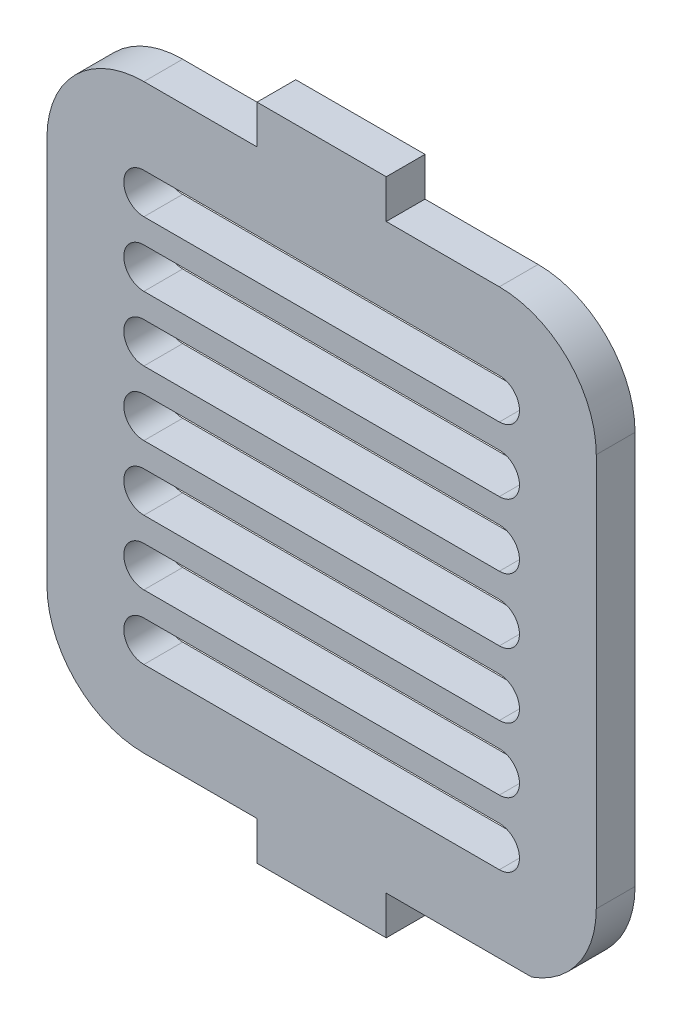
SolidWorks part; units mm, degrees
ref_plane "Front Plane" through (0, 0, 0) normal (0, 0, 1) x (1, 0, 0)
ref_plane "Top Plane" through (0, 0, 0) normal (0, 1, 0) x (1, 0, 0)
ref_plane "Right Plane" through (0, 0, 0) normal (1, 0, 0) x (0, 0, -1)
sketch "Sketch1" plane through (0, 0, 0) normal (0, 0, 1) x (1, 0, 0)
  line L0 (10, 45) -> (10, 51)
  line L3 (10, 51) -> (-10, 51)
  line L4 (-10, 51) -> (-10, 45)
  line L5 (10, -45) -> (10, -51)
  line L6 (10, -51) -> (-10, -51)
  line L7 (-10, -51) -> (-10, -45)
  line L9 (42.5, 30) -> (42.5, -30.8579)
  line L11 (-42.5, -30) -> (-42.5, 30)
  line L12 (-27.5, 30) -> (27.5, 30) construction
  line L13 (-27.5, 33.1127) -> (27.5, 33.1127)
  line L14 (-27.5, 26.8873) -> (27.5, 26.8873)
  line L15 (-27.5, 20) -> (27.5, 20) construction
  line L16 (-27.5, 23.1127) -> (27.5, 23.1127)
  line L17 (-27.5, 16.8873) -> (27.5, 16.8873)
  line L18 (-27.5, 10) -> (27.5, 10) construction
  line L19 (-27.5, 13.1127) -> (27.5, 13.1127)
  line L20 (-27.5, 6.8873) -> (27.5, 6.8873)
  line L21 (-27.5, 0) -> (27.5, 0) construction
  line L22 (-27.5, 3.1127) -> (27.5, 3.1127)
  line L23 (-27.5, -3.1127) -> (27.5, -3.1127)
  line L24 (-27.5, -10) -> (27.5, -10) construction
  line L25 (-27.5, -6.8873) -> (27.5, -6.8873)
  line L26 (-27.5, -13.1127) -> (27.5, -13.1127)
  line L27 (-27.5, -20) -> (27.5, -20) construction
  line L28 (-27.5, -16.8873) -> (27.5, -16.8873)
  line L29 (-27.5, -23.1127) -> (27.5, -23.1127)
  line L30 (-27.5, -30) -> (27.5, -30) construction
  line L31 (-27.5, -26.8873) -> (27.5, -26.8873)
  line L32 (-27.5, -33.1127) -> (27.5, -33.1127)
  line L33 (-27.5, 45) -> (27.5, 45)
  line L34 (-10, 45) -> (10, 45)
  line L35 (-27.5, -45) -> (32.5, -45)
  line L36 (-10, -45) -> (10, -45)
  arc A0 (-42.5, 30) -> (-27.5, 45) centre (-27.5, 30) cw
  arc A1 (-27.5, -45) -> (-42.5, -30) centre (-27.5, -30) cw
  arc A2 (42.5, -30.8579) -> (32.5, -45) centre (27.5, -30.8579) cw
  arc A3 (27.5, 45) -> (42.5, 30) centre (27.5, 30) cw
  arc A4 (-27.5, 33.1127) -> (-27.5, 26.8873) centre (-27.5, 30) ccw
  arc A5 (27.5, 26.8873) -> (27.5, 33.1127) centre (27.5, 30) ccw
  arc A6 (-27.5, 23.1127) -> (-27.5, 16.8873) centre (-27.5, 20) ccw
  arc A7 (27.5, 16.8873) -> (27.5, 23.1127) centre (27.5, 20) ccw
  arc A8 (-27.5, 13.1127) -> (-27.5, 6.8873) centre (-27.5, 10) ccw
  arc A9 (27.5, 6.8873) -> (27.5, 13.1127) centre (27.5, 10) ccw
  arc A10 (-27.5, 3.1127) -> (-27.5, -3.1127) centre (-27.5, 0) ccw
  arc A11 (27.5, -3.1127) -> (27.5, 3.1127) centre (27.5, 0) ccw
  arc A12 (-27.5, -6.8873) -> (-27.5, -13.1127) centre (-27.5, -10) ccw
  arc A13 (27.5, -13.1127) -> (27.5, -6.8873) centre (27.5, -10) ccw
  arc A14 (-27.5, -16.8873) -> (-27.5, -23.1127) centre (-27.5, -20) ccw
  arc A15 (27.5, -23.1127) -> (27.5, -16.8873) centre (27.5, -20) ccw
  arc A16 (-27.5, -26.8873) -> (-27.5, -33.1127) centre (-27.5, -30) ccw
  arc A17 (27.5, -33.1127) -> (27.5, -26.8873) centre (27.5, -30) ccw
  point P4 (0, 0)
  point P16 (-45, 45)
  point P19 (-45, -45)
  point P22 (45, -45)
  point P25 (0, 30)
  point P31 (0, 45)
  point P33 (0, 20)
  point P40 (0, 10)
  point P47 (0, 0)
  point P54 (0, -10)
  point P61 (0, -20)
  point P68 (0, -30)
  dimension "D5" = 15
  dimension "D6" = 15
  dimension "D1" = 6
  dimension "D2" = 6
  dimension "D3" = 90
  dimension "D4" = 55
  dimension "D7" = 7
extrude "Boss-Extrude1" add sketch "Sketch1" along normal blind 6 contours A3 L33 A0 L11 A1 L35 A2 L9 A17 L32 A16 L31 A15 L29 A14 L28 A13 L26 A12 L25 A11 L23 A10 L22 A9 L20 A8 L19 A7 L17 A6 L16 A5 L14 A4 L13 | L4 L33 L0 L3 | L35 L7 L6 L5
